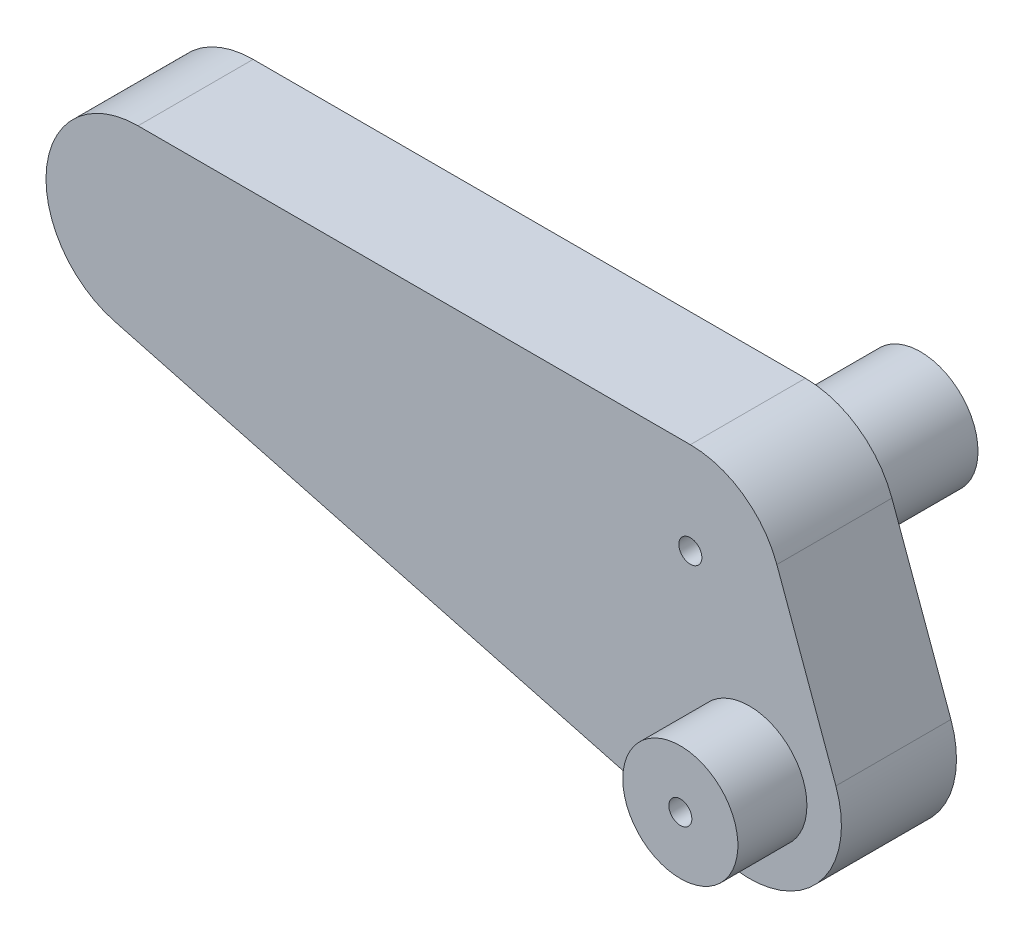
SolidWorks part; units mm, degrees
material "ABS"
ref_plane "Front Plane" through (0, 0, 0) normal (0, 0, 1) x (1, 0, 0)
ref_plane "Top Plane" through (0, 0, 0) normal (0, 1, 0) x (1, 0, 0)
ref_plane "Right Plane" through (0, 0, 0) normal (1, 0, 0) x (0, 0, -1)
sketch "Sketch1" plane through (0, 0, 0) normal (0, 0, 1) x (1, 0, 0)
  line L0 (0, 0) -> (-24, 0)
  line L1 (0, 0) -> (2.5652, -7.0477)
  dimension "D1" = 24
  dimension "D2" = 7.5
  dimension "D3" = 110
sketch "Sketch2" plane through (0, 0, 0) normal (0, 0, 1) x (1, 0, 0)
  line L0 (-24, 4) -> (0, 4)
  line L1 (3.7588, 1.3681) -> (6.3239, -5.6796)
  line L2 (1.5394, -10.9139) -> (-25.0257, -3.8663)
  circle A0 centre (-24, 0) radius 2.5
  arc A1 (-24, 4) -> (-25.0257, -3.8663) centre (-24, 0) ccw
  circle A2 centre (0, 0) radius 2.5
  arc A3 (3.7588, 1.3681) -> (0, 4) centre (0, 0) ccw
  circle A4 centre (2.5652, -7.0477) radius 2.5
  arc A5 (1.5394, -10.9139) -> (6.3239, -5.6796) centre (2.5652, -7.0477) ccw
  dimension "D1" = 5
  dimension "D2" = 8
  dimension "D3" = 5
  dimension "D4" = 8
  dimension "D5" = 5
  dimension "D6" = 8
extrude "Boss-Extrude1" add sketch "Sketch2" along normal blind 5
sketch "Sketch3" plane through (0, 0, 5) normal (0, 0, 1) x (1, 0, 0)
  circle A0 centre (0, 0) radius 2.5
  circle A1 centre (0, 0) radius 0.5
  dimension "D1" = 5
  dimension "D2" = 1
extrude "Boss-Extrude2" add sketch "Sketch3" against normal blind 10
sketch "Sketch4" plane through (0, 0, 0) normal (0, 0, -1) x (-1, 0, 0)
  circle A0 centre (-2.5652, -7.0477) radius 2.5
  circle A1 centre (-2.5652, -7.0477) radius 0.5
  dimension "D1" = 1
  dimension "D2" = 5
extrude "Boss-Extrude3" add sketch "Sketch4" against normal blind 8
sketch "Sketch5" plane through (0, 0, 0) normal (0, 0, -1) x (-1, 0, 0)
  circle A0 centre (24, 0) radius 2.5
  dimension "D1" = 5
extrude "Boss-Extrude4" add sketch "Sketch5" against normal blind 5
